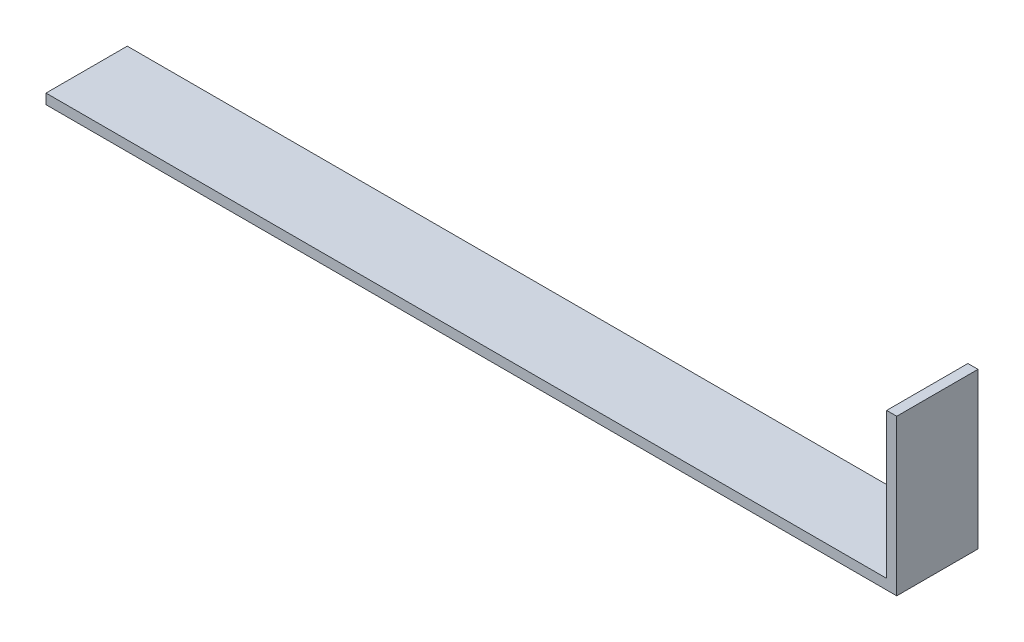
SolidWorks part; units mm, degrees
ref_plane "Alzado" through (0, 0, 0) normal (0, 0, 1) x (1, 0, 0)
ref_plane "Planta" through (0, 0, 0) normal (0, 1, 0) x (1, 0, 0)
ref_plane "Vista lateral" through (0, 0, 0) normal (1, 0, 0) x (0, 0, -1)
sketch "Croquis1" plane through (0, 0, 0) normal (0, 0, 1) x (1, 0, 0)
  line L0 (0, 0) -> (202.9376, 0)
  line L1 (202.9376, 0) -> (202.9376, 90.92)
  line L2 (202.9376, 90.92) -> (297.64, 90.92)
  line L3 (0, -6.31) -> (209.2476, -6.31)
  line L4 (209.2476, -6.31) -> (209.2476, 84.61)
  line L5 (209.2476, 84.61) -> (297.64, 84.61)
  line L6 (0, 0) -> (0, -6.31)
  line L7 (297.64, 90.92) -> (297.64, 84.61)
  dimension "D1" = 297.64
  dimension "D2" = 90.92
  dimension "D3" = 6.31
extrude "Saliente-Extruir1" add sketch "Croquis1" along normal blind 50.8
sketch "Croquis4" plane through (0, 84.61, 0) normal (0, -1, 0) x (1, 0, 0)
  line L0 (209.2476, 0) -> (209.2476, 50.8)
  line L1 (209.2476, 50.8) -> (297.64, 50.8)
  line L2 (297.64, 50.8) -> (297.64, 0)
  line L3 (297.64, 0) -> (209.2476, 0)
extrude "Cortar-Extruir2" cut sketch "Croquis4" against normal blind 6.31
sketch "Croquis5" plane through (0, 0, 0) normal (-1, 0, 0) x (0, 0, 1)
  line L0 (0, 0) -> (50.8, 0)
  line L1 (50.8, 0) -> (50.8, -6.31)
  line L2 (50.8, -6.31) -> (0, -6.31)
  line L3 (0, -6.31) -> (0, 0)
extrude "Saliente-Extruir2" add sketch "Croquis5" along normal blind 322.45
sketch "Croquis7" plane through (202.9376, 0, 0) normal (-1, 0, 0) x (0, 0, 1)
  line L0 (50.8, 90.92) -> (50.8, 94.8116)
  line L1 (50.8, 90.92) -> (50.8, 0) construction
  line L2 (50.8, 94.8116) -> (100.8, 94.8116)
  line L3 (100.8, 94.8116) -> (100.8, 90.92)
  line L4 (100.8, 90.92) -> (50.8, 90.92)
  dimension "D1" = 50
sketch "Croquis8" plane through (0, 5, 0) normal (0, -1, 0) x (-1, 0, 0)
  line L0 (330.5578, -31.75) -> (330.5578, -25.4) construction
  line L1 (330.5578, -25.4) -> (362.5578, -25.4) construction
  circle A0 centre (330.5578, -25.4) radius 6.35 construction
  circle A1 centre (330.5578, -25.4) radius 6.35
  circle A2 centre (362.5578, -25.4) radius 6.35
sketch "Croquis9" plane through (0, -6.31, 0) normal (0, -1, 0) x (-1, 0, 0)
  circle A0 centre (362.5578, -25.4) radius 6.35
  circle A1 centre (330.5578, -25.4) radius 6.35
